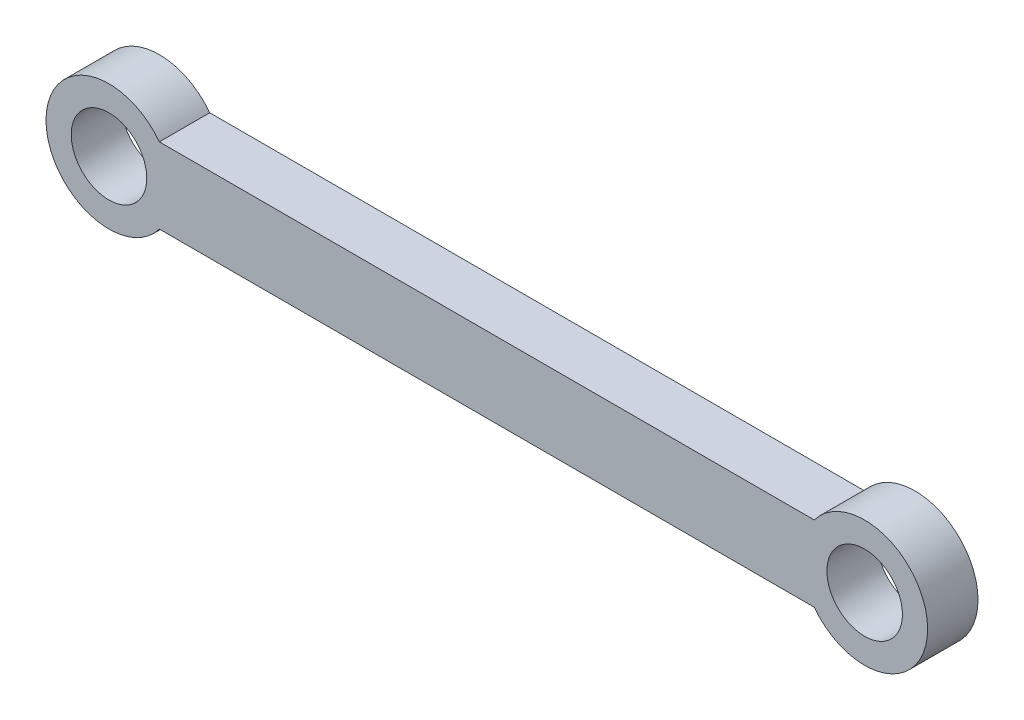
SolidWorks part; units mm, degrees
ref_plane "정면" through (0, 0, 0) normal (0, 0, 1) x (1, 0, 0)
ref_plane "윗면" through (0, 0, 0) normal (0, 1, 0) x (1, 0, 0)
ref_plane "우측면" through (0, 0, 0) normal (1, 0, 0) x (0, 0, -1)
sketch "스케치1" plane through (0, 0, 0) normal (0, 0, 1) x (1, 0, 0)
  line L0 (-15, 0) -> (15, 0) construction
  line L1 (-13, -1.5) -> (13, -1.5)
  line L2 (-13, 1.5) -> (13, 1.5)
  line L3 (-15, 1.5) -> (15, 1.5) construction
  line L4 (-15, -1.5) -> (15, -1.5) construction
  circle A0 centre (-15, 0) radius 1.5
  circle A1 centre (15, 0) radius 1.5
  arc A2 (-13, 1.5) -> (-13, -1.5) centre (-15, 0) ccw
  arc A3 (13, -1.5) -> (13, 1.5) centre (15, 0) ccw
  point P3 (0, 0)
extrude "보스-돌출1" add sketch "스케치1" along normal blind 2
